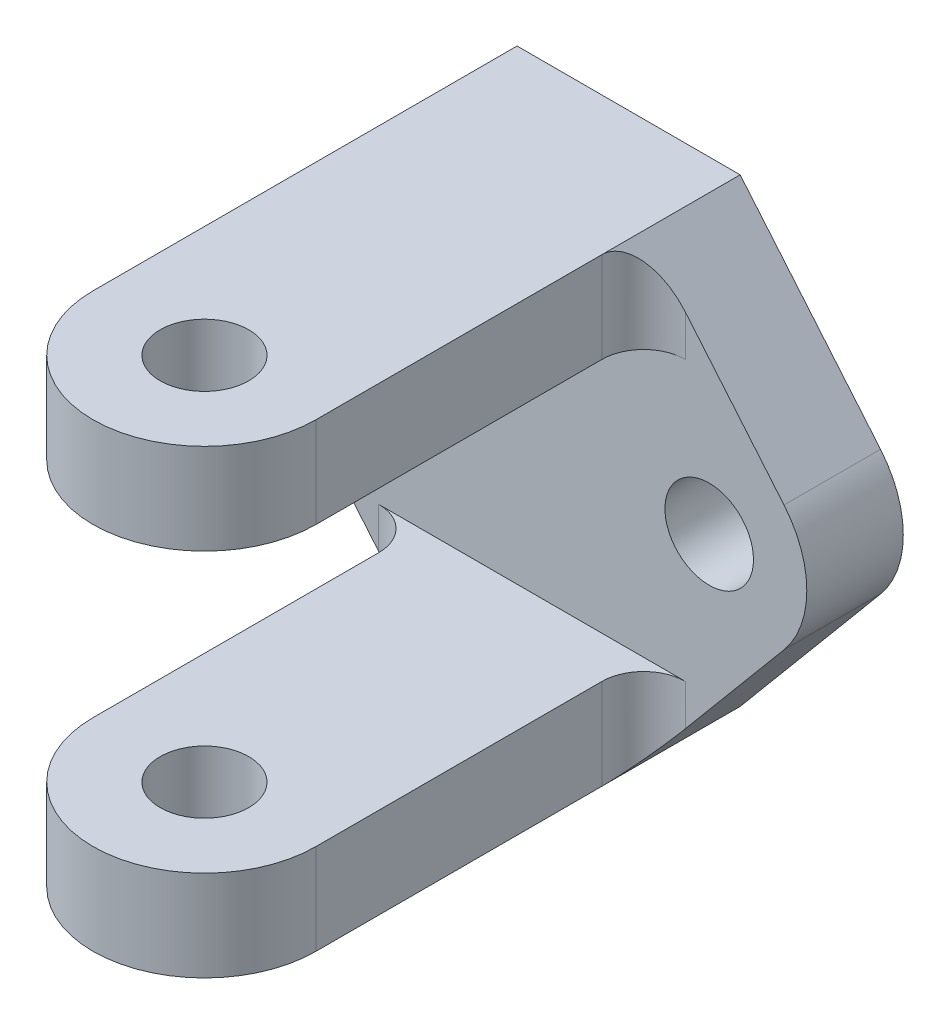
SolidWorks part; units mm, degrees
material "7075-T6 (SN)"
ref_plane "Front Plane" through (0, 0, 0) normal (0, 0, 1) x (1, 0, 0)
ref_plane "Top Plane" through (0, 0, 0) normal (0, 1, 0) x (1, 0, 0)
ref_plane "Right Plane" through (0, 0, 0) normal (1, 0, 0) x (0, 0, -1)
sketch "Sketch1" plane through (0, 0, 0) normal (0, 0, 1) x (1, 0, 0)
  line L0 (12.7, 0) -> (-12.7, 0) construction
  line L1 (-20.7, -16.51) -> (20.7, -16.51)
  line L2 (-20.7, -16.51) -> (-20.7, 16.51)
  line L3 (-20.7, 16.51) -> (20.7, 16.51)
  line L4 (20.7, -16.51) -> (20.7, 16.51)
  line L5 (-20.7, -16.51) -> (20.7, 16.51) construction
  line L6 (-20.7, 16.51) -> (20.7, -16.51) construction
  circle A0 centre (12.7, 0) radius 3.175
  circle A1 centre (-12.7, 0) radius 3.175
  point P0 (0, 0)
  dimension "D1" = 6.35
  dimension "D2" = 25.4
  dimension "D3" = 8
  dimension "D4" = 16.51
extrude "Boss-Extrude1" add sketch "Sketch1" along normal blind 12 contours L3 L4 L1 L2
sketch "Sketch2" plane through (0, 0, 12) normal (0, 0, 1) x (1, 0, 0)
  line L0 (-12.7, 0) -> (12.7, 0) construction
  line L2 (-20.7, 10) -> (20.7, 10)
  line L3 (-20.7, 10) -> (-20.7, 16.51)
  line L4 (-20.7, 16.51) -> (20.7, 16.51)
  line L5 (20.7, 10) -> (20.7, 16.51)
  line L6 (-20.7, 10) -> (20.7, 16.51) construction
  line L7 (-20.7, 16.51) -> (20.7, 10) construction
  line L8 (-20.7, 16.51) -> (-20.7, -16.51) construction
  line L9 (20.7, -10) -> (20.7, -16.51)
  line L10 (-20.7, -10) -> (-20.7, -16.51)
  line L11 (-20.7, -16.51) -> (20.7, -10) construction
  line L12 (-20.7, -10) -> (20.7, -16.51) construction
  line L13 (-20.7, -10) -> (20.7, -10)
  line L14 (-20.7, -16.51) -> (20.7, -16.51)
  circle A0 centre (-12.7, 0) radius 3.175 construction
  circle A1 centre (12.7, 0) radius 3.175 construction
  point P6 (0, 13.255)
  point P21 (0, -13.255)
  dimension "D1" = 20
extrude "Boss-Extrude2" add sketch "Sketch2" along normal blind 53
sketch "Sketch3" plane through (0, 0, 0) normal (0, 1, 0) x (1, 0, 0)
  point P0 (0, -35.5)
  dimension "D1" = 35.5
ref_point "UBJ Point"
sketch "Sketch4" plane through (0, 0, 0) normal (0, 1, 0) x (1, 0, 0)
  circle A0 centre (0, -35.5) radius 3.175
  dimension "D1" = 6.35
extrude "Cut-Extrude1" cut sketch "Sketch4" against normal up to surface and the other way up to surface up to face at (0, -16.51, 32.5) other way up to face at (0, 16.51, 32.5)
sketch "Sketch5" plane through (0, 0, 0) normal (0, 1, 0) x (1, 0, 0)
  line L0 (20.7, -12) -> (8.3595, -39.2814)
  line L1 (-8.3595, -39.2814) -> (-20.7, -12)
  line L4 (20.7, 0) -> (-20.7, 0)
  line L5 (-20.7, 0) -> (-20.7, -65)
  line L6 (-20.7, -65) -> (20.7, -65)
  line L7 (20.7, -65) -> (20.7, 0)
  line L9 (-20.7, -12) -> (-20.7, -65)
  line L10 (-20.7, -65) -> (20.7, -65)
  line L11 (20.7, -65) -> (20.7, -12)
  line L12 (20.7, -12) -> (-20.7, -12)
  line L13 (20.7, -65) -> (20.7, -12)
  line L14 (-20.7, -65) -> (20.7, -65)
  line L15 (-20.7, -12) -> (-20.7, -65)
  line L17 (20.7, -65) -> (20.7, -12)
  line L18 (-20.7, -65) -> (20.7, -65)
  line L19 (-20.7, -12) -> (-20.7, -65)
  arc A0 (-8.3595, -39.2814) -> (8.3595, -39.2814) centre (0, -35.5) ccw
  circle A1 centre (0, -35.5) radius 3.175 construction
  circle A2 centre (0, -35.5) radius 3.175 construction
  dimension "D3" = 6
  dimension "D1" = 0
  dimension "D2" = 0
extrude "Cut-Extrude2" [suppressed] cut sketch "Sketch5" against normal up to surface and the other way up to surface contours A0 L1 L9 L10 L11 L0
sketch "Sketch6" plane through (0, 0, 0) normal (0, 1, 0) x (1, 0, 0)
  line L0 (-8, -35.5) -> (-8, -20)
  line L1 (8, -35.5) -> (8, -20)
  line L2 (-16, -12) -> (-20.7, -12)
  line L3 (-8, -20) -> (-8, -12)
  line L4 (20.7, -12) -> (-20.7, -12)
  line L5 (-20.7, -12) -> (-20.7, -65)
  line L6 (-20.7, -65) -> (20.7, -65)
  line L7 (20.7, -65) -> (20.7, -12)
  line L8 (20.7, -12) -> (16, -12)
  line L9 (-20.7, -12) -> (-20.7, -65)
  line L10 (-20.7, -65) -> (20.7, -65)
  line L11 (20.7, -65) -> (20.7, -12)
  line L12 (-8, -12) -> (-16, -12)
  line L13 (8, -20) -> (8, -12)
  line L14 (8, -12) -> (16, -12)
  arc A0 (-8, -35.5) -> (8, -35.5) centre (0, -35.5) ccw
  circle A1 centre (0, -35.5) radius 3.175 construction
  arc A2 (-8, -20) -> (-16, -12) centre (-16, -20) ccw construction
  arc A3 (8, -20) -> (16, -12) centre (16, -20) cw construction
  dimension "D2" = 8
  dimension "D3" = 8
  dimension "D1" = 0
extrude "Cut-Extrude3" cut sketch "Sketch6" against normal up to surface and the other way up to surface up to face at (0, -16.51, 38.675) other way up to face at (0, 16.51, 32.325)
fillet "Fillet1" [suppressed] radius 12.7
sketch "Sketch7" plane through (0, 0, 0) normal (0, 0, 1) x (1, 0, 0)
  line L0 (-12.7, 7) -> (-8, 7)
  line L1 (-12.7, -7) -> (-8, -7)
  line L2 (-8, 16.51) -> (-8, 7)
  line L3 (-8, -16.51) -> (-8, -7)
  line L4 (0, 10.3988) -> (0, -8.4154) construction
  line L5 (8, -16.51) -> (8, -7)
  line L6 (20.7, -16.51) -> (8, -16.51)
  line L7 (20.7, 16.51) -> (20.7, -16.51)
  line L8 (8, 16.51) -> (20.7, 16.51)
  line L9 (8, 16.51) -> (8, 7)
  line L10 (12.7, 7) -> (8, 7)
  line L11 (12.7, -7) -> (8, -7)
  line L12 (8, 10) -> (-8, 10)
  line L13 (-8, 10) -> (-8, 16.51)
  line L14 (-8, 16.51) -> (-20.7, 16.51)
  line L15 (-20.7, 16.51) -> (-20.7, -16.51)
  line L16 (-20.7, -16.51) -> (-8, -16.51)
  line L17 (-8, -16.51) -> (-8, -10)
  line L18 (-8, -10) -> (8, -10)
  line L19 (8, -10) -> (8, -16.51)
  line L20 (8, -16.51) -> (20.7, -16.51)
  line L21 (20.7, -16.51) -> (20.7, 16.51)
  line L22 (20.7, 16.51) -> (8, 16.51)
  line L23 (8, 16.51) -> (8, 10)
  line L26 (-8, 16.51) -> (-20.7, 16.51)
  line L27 (-20.7, 16.51) -> (-20.7, -16.51)
  line L28 (-20.7, -16.51) -> (-8, -16.51)
  line L32 (8, -16.51) -> (20.7, -16.51)
  line L33 (20.7, -16.51) -> (20.7, 16.51)
  line L34 (20.7, 16.51) -> (8, 16.51)
  line L36 (-8, 10) -> (8, 10) construction
  line L37 (8, -10) -> (-8, -10) construction
  line L38 (-8, 10) -> (8, 10)
  line L39 (8, -10) -> (-8, -10)
  arc A0 (-12.7, 7) -> (-12.7, -7) centre (-12.7, 0) ccw
  circle A1 centre (-12.7, 0) radius 3.175 construction
  arc A2 (12.7, 7) -> (12.7, -7) centre (12.7, 0) cw
  dimension "D2" = 7
  dimension "D1" = 0
extrude "Cut-Extrude4" cut sketch "Sketch7" along normal up to surface (12 mm away) contours A0 L0 L2 L26 L27 L28 L3 L1 | L10 A2 L11 L5 L6 L7 L8 L9 up to face at (0, 0, 12)
fillet "Fillet2" [suppressed] radius 5
sketch "Sketch8" plane through (0, 0, 0) normal (0, 0, 1) x (1, 0, 0)
  line L0 (12.7, 7) -> (8, 7) construction
  line L1 (8, 16.51) -> (8, 7) construction
  line L2 (12.7, 7) -> (8, 7)
  line L3 (8, 16.51) -> (8, 7)
  line L4 (6.7586, 0) -> (-5.803, 0) construction
  line L5 (0, 7.1591) -> (0, -7.1591) construction
  line L6 (8, 16.51) -> (18.0658, 4.4954)
  line L7 (-8, 16.51) -> (-8, 7)
  line L8 (-12.7, 7) -> (-8, 7)
  line L9 (-8, 16.51) -> (-18.0658, 4.4954)
  line L10 (-8, -16.51) -> (-18.0658, -4.4954)
  line L11 (-12.7, -7) -> (-8, -7)
  line L12 (-8, -16.51) -> (-8, -7)
  line L13 (8, -16.51) -> (8, -7)
  line L14 (12.7, -7) -> (8, -7)
  line L15 (8, -16.51) -> (18.0658, -4.4954)
  arc A0 (12.7, -7) -> (12.7, 7) centre (12.7, 0) ccw construction
  arc A1 (18.0658, 4.4954) -> (12.7, 7) centre (12.7, 0) ccw
  arc A2 (-18.0658, 4.4954) -> (-12.7, 7) centre (-12.7, 0) cw
  arc A3 (-18.0658, -4.4954) -> (-12.7, -7) centre (-12.7, 0) ccw
  arc A4 (18.0658, -4.4954) -> (12.7, -7) centre (12.7, 0) cw
extrude "Boss-Extrude3" add sketch "Sketch8" along normal up to surface (12 mm away) contours L15 A4 L14 L13 | A3 L10 L12 L11 | L6 A1 L2 L3 | L9 A2 L8 L7 up to face at (-9.525, 0, 12)
fillet "Fillet3" radius 3 4 edges at (8, 13.255, 12) (-8, 13.255, 12) (-8, -13.255, 12) (8, -13.255, 12)
sketch "Sketch10" plane through (0, 0, 0) normal (0, 0, 1) x (1, 0, 0)
  line L6 (-8, 16.51) -> (-18.0658, 4.4954)
  line L7 (8, 16.51) -> (-8, 16.51)
  line L8 (18.0658, 4.4954) -> (8, 16.51)
  line L9 (8, -16.51) -> (18.0658, -4.4954)
  line L10 (-8, -16.51) -> (8, -16.51)
  line L11 (-18.0658, -4.4954) -> (-8, -16.51)
  line L12 (-8, 16.51) -> (-18.0658, 4.4954)
  line L13 (8, 16.51) -> (-8, 16.51)
  line L14 (18.0658, 4.4954) -> (8, 16.51)
  line L15 (8, -16.51) -> (18.0658, -4.4954)
  line L16 (-8, -16.51) -> (8, -16.51)
  line L17 (-18.0658, -4.4954) -> (-8, -16.51)
  arc A2 (-18.0658, 4.4954) -> (-18.0658, -4.4954) centre (-12.7, 0) ccw
  arc A3 (18.0658, -4.4954) -> (18.0658, 4.4954) centre (12.7, 0) ccw
  arc A4 (-18.0658, 4.4954) -> (-18.0658, -4.4954) centre (-12.7, 0) ccw
  arc A5 (18.0658, -4.4954) -> (18.0658, 4.4954) centre (12.7, 0) ccw
  dimension "D1" = 0
extrude "Cut-Extrude5" cut sketch "Sketch10" along normal blind 5.08
